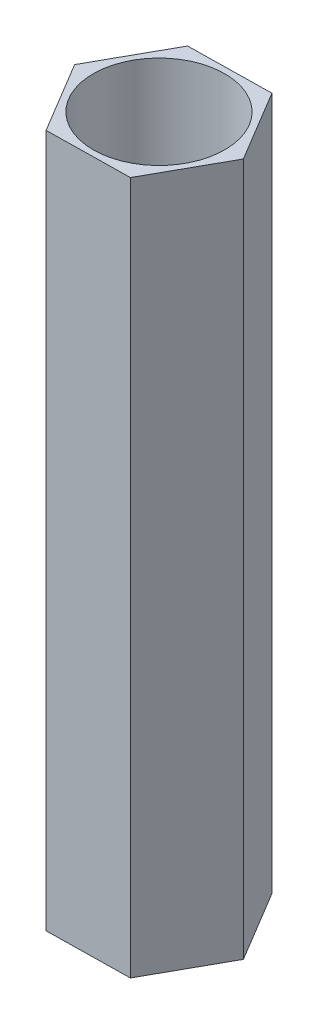
SolidWorks part; units mm, degrees
ref_plane "Front Plane" through (0, 0, 0) normal (0, 0, 1) x (1, 0, 0)
ref_plane "Top Plane" through (0, 0, 0) normal (0, 1, 0) x (1, 0, 0)
ref_plane "Right Plane" through (0, 0, 0) normal (1, 0, 0) x (0, 0, -1)
sketch "Sketch1" plane through (0, 0, 0) normal (0, 1, 0) x (1, 0, 0)
  line L1 (1.231, -2.0556) -> (2.3957, 0.0383)
  line L2 (2.3957, 0.0383) -> (1.1647, 2.0939)
  line L3 (1.1647, 2.0939) -> (-1.231, 2.0556)
  line L4 (-1.231, 2.0556) -> (-2.3957, -0.0383)
  line L5 (-2.3957, -0.0383) -> (-1.1647, -2.0939)
  line L6 (-1.1647, -2.0939) -> (1.231, -2.0556)
  circle A0 centre (0, 0) radius 2.075 construction
  dimension "D1" = 4.15
extrude "Boss-Extrude1" add sketch "Sketch1" along normal blind 20
sketch "Sketch2" plane through (0, 20, 0) normal (0, 1, 0) x (1, 0, 0)
  circle A0 centre (0, 0) radius 1.9
extrude "Cut-Extrude1" cut sketch "Sketch2" against normal blind 7.5
sketch "Sketch3" plane through (0, 0, 0) normal (0, -1, 0) x (1, 0, 0)
  circle A0 centre (0, 0) radius 1.9
extrude "Cut-Extrude2" cut sketch "Sketch3" against normal blind 7.5
